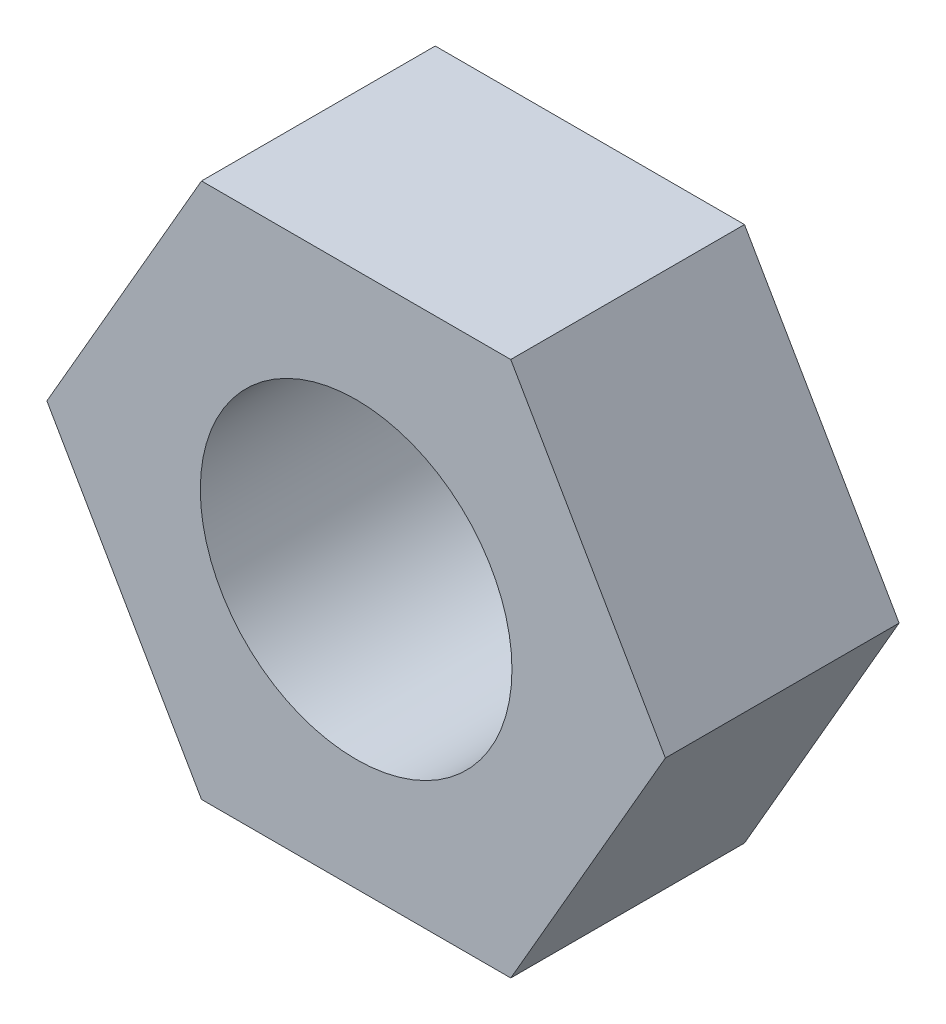
SolidWorks part; units mm, degrees
ref_plane "前视基准面" through (0, 0, 0) normal (0, 0, 1) x (1, 0, 0)
ref_plane "上视基准面" through (0, 0, 0) normal (0, 1, 0) x (1, 0, 0)
ref_plane "右视基准面" through (0, 0, 0) normal (1, 0, 0) x (0, 0, -1)
other "Configuration Table"
sketch "草图1" plane through (0, 0, 0) normal (0, 0, 1) x (1, 0, 0)
  line L0 (3.1754, 0) -> (1.5877, 2.75)
  line L1 (1.5877, 2.75) -> (-1.5877, 2.75)
  line L2 (-1.5877, 2.75) -> (-3.1754, 0)
  line L3 (-3.1754, 0) -> (-1.5877, -2.75)
  line L4 (-1.5877, -2.75) -> (1.5877, -2.75)
  line L5 (1.5877, -2.75) -> (3.1754, 0)
  circle A0 centre (0, 0) radius 1.6
extrude "M3螺母" add sketch "草图1" along normal blind 2.4
